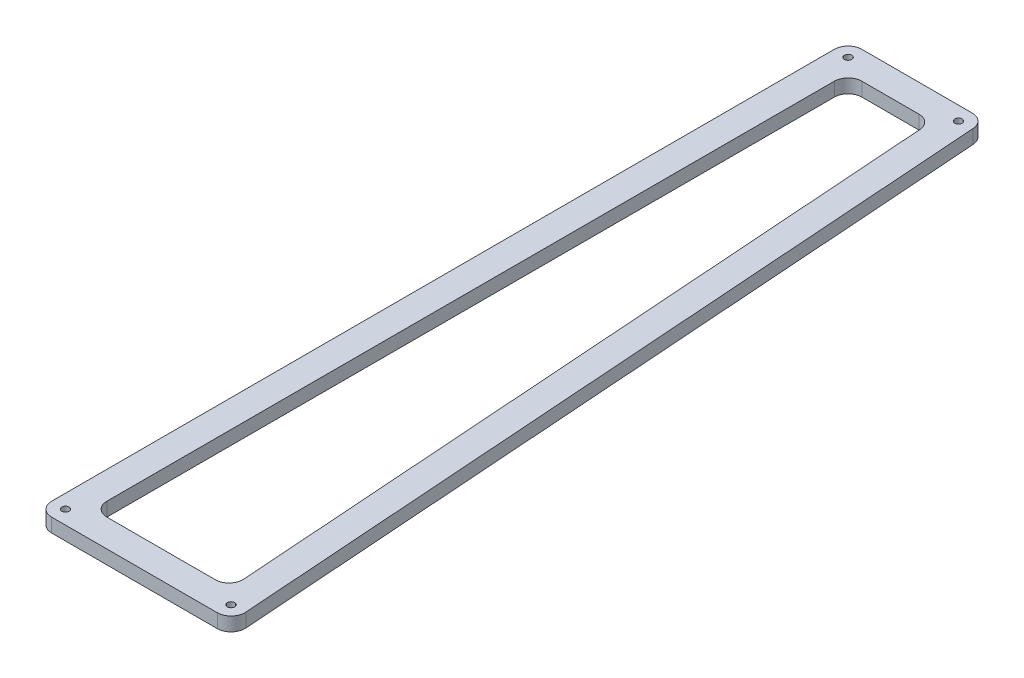
SolidWorks part; units mm, degrees
ref_plane "Front Plane" through (0, 0, 0) normal (0, 0, 1) x (1, 0, 0)
ref_plane "Top Plane" through (0, 0, 0) normal (0, 1, 0) x (1, 0, 0)
ref_plane "Right Plane" through (0, 0, 0) normal (1, 0, 0) x (0, 0, -1)
sketch "Sketch1" plane through (0, 0, 0) normal (0, 1, 0) x (1, 0, 0)
  line L0 (-3.175, 180.086) -> (-3.175, 0)
  line L1 (0, -3.175) -> (38.1, -3.175)
  line L2 (41.2671, 0.2234) -> (28.5671, 180.3094)
  line L3 (25.4, 183.261) -> (0, 183.261)
  line L4 (3.175, 173.736) -> (3.175, 6.35)
  line L5 (6.35, 3.175) -> (31.2864, 3.175)
  line L6 (34.4535, 6.5734) -> (22.6492, 173.9594)
  line L7 (19.482, 176.911) -> (6.35, 176.911)
  arc A0 (3.175, 6.35) -> (6.35, 3.175) centre (6.35, 6.35) ccw
  arc A1 (3.175, 173.736) -> (6.35, 176.911) centre (6.35, 173.736) cw
  arc A2 (22.6492, 173.9594) -> (19.482, 176.911) centre (19.482, 173.736) ccw
  arc A3 (31.2864, 3.175) -> (34.4535, 6.5734) centre (31.2864, 6.35) ccw
  arc A4 (-3.175, 0) -> (0, -3.175) centre (0, 0) ccw
  arc A5 (-3.175, 180.086) -> (0, 183.261) centre (0, 180.086) cw
  arc A6 (38.1, -3.175) -> (41.2671, 0.2234) centre (38.1, 0) ccw
  arc A7 (28.5671, 180.3094) -> (25.4, 183.261) centre (25.4, 180.086) ccw
  circle A8 centre (0, 180.086) radius 0.8509
  circle A9 centre (25.4, 180.086) radius 0.8509
  circle A10 centre (38.1, 0) radius 0.8509
  circle A11 centre (0, 0) radius 0.8509
  point P0 (0, 0)
  point P1 (38.1, 0)
  point P3 (25.4, 180.086)
  point P4 (0, 180.086)
  dimension "D13" = 3.175
  dimension "D14" = 1.7018
  dimension "D1" = 38.1
  dimension "D2" = 25.4
  dimension "D3" = 180.086
  dimension "D4" = 3.175
  dimension "D5" = 3.175
  dimension "D6" = 3.175
  dimension "D7" = 3.175
  dimension "D8" = 3.175
  dimension "D9" = 6.35
  dimension "D10" = 6.35
  dimension "D11" = 6.35
  dimension "D12" = 6.35
extrude "Boss-Extrude1" add sketch "Sketch1" along normal blind 3.175
